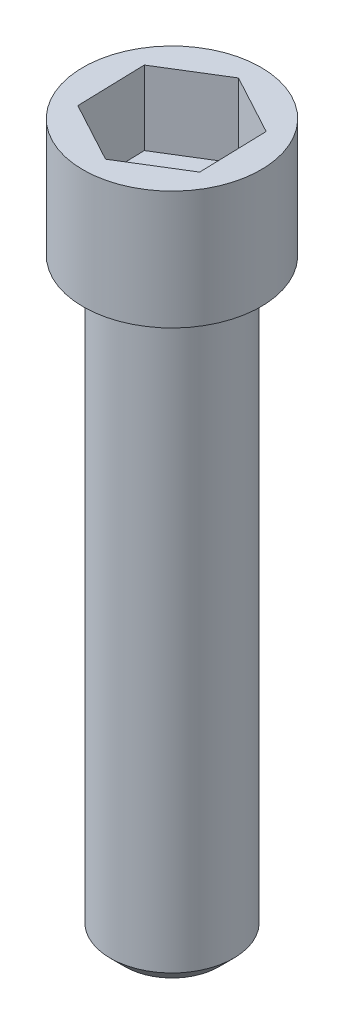
SolidWorks part; units mm, degrees
material "Plain Carbon Steel"
ref_plane "Front" through (0, 0, 0) normal (0, 0, 1) x (1, 0, 0)
ref_plane "Top" through (0, 0, 0) normal (0, 1, 0) x (1, 0, 0)
ref_plane "Right" through (0, 0, 0) normal (1, 0, 0) x (0, 0, -1)
sketch "Sketch1" plane through (0, 0, 0) normal (0, 1, 0) x (1, 0, 0)
  circle A0 centre (0, 0) radius 1.04
  dimension "D1" = 2.08
extrude "Boss-Extrude1" add sketch "Sketch1" along normal blind 10
sketch "Sketch2" plane through (0, 10, 0) normal (0, 1, 0) x (1, 0, 0)
  circle A0 centre (0, 0) radius 1.5
  dimension "D1" = 3
extrude "Boss-Extrude2" add sketch "Sketch2" along normal blind 2
sketch "Sketch3" plane through (0, 12, 0) normal (0, 1, 0) x (1, 0, 0)
  line L1 (-0.0328, 1.1542) -> (-1.016, 0.5487)
  line L2 (-1.016, 0.5487) -> (-0.9832, -0.6055)
  line L3 (-0.9832, -0.6055) -> (0.0328, -1.1542)
  line L4 (0.0328, -1.1542) -> (1.016, -0.5487)
  line L5 (1.016, -0.5487) -> (0.9832, 0.6055)
  line L6 (0.9832, 0.6055) -> (-0.0328, 1.1542)
  circle A0 centre (0, 0) radius 1 construction
  dimension "D1" = 2
  dimension "D2" = 0.9832
extrude "Cut-Extrude1" cut sketch "Sketch3" against normal blind 1.25
chamfer "Chamfer1" distance 0.25 angle 45 1 edges at (0, 0, 1.04)
